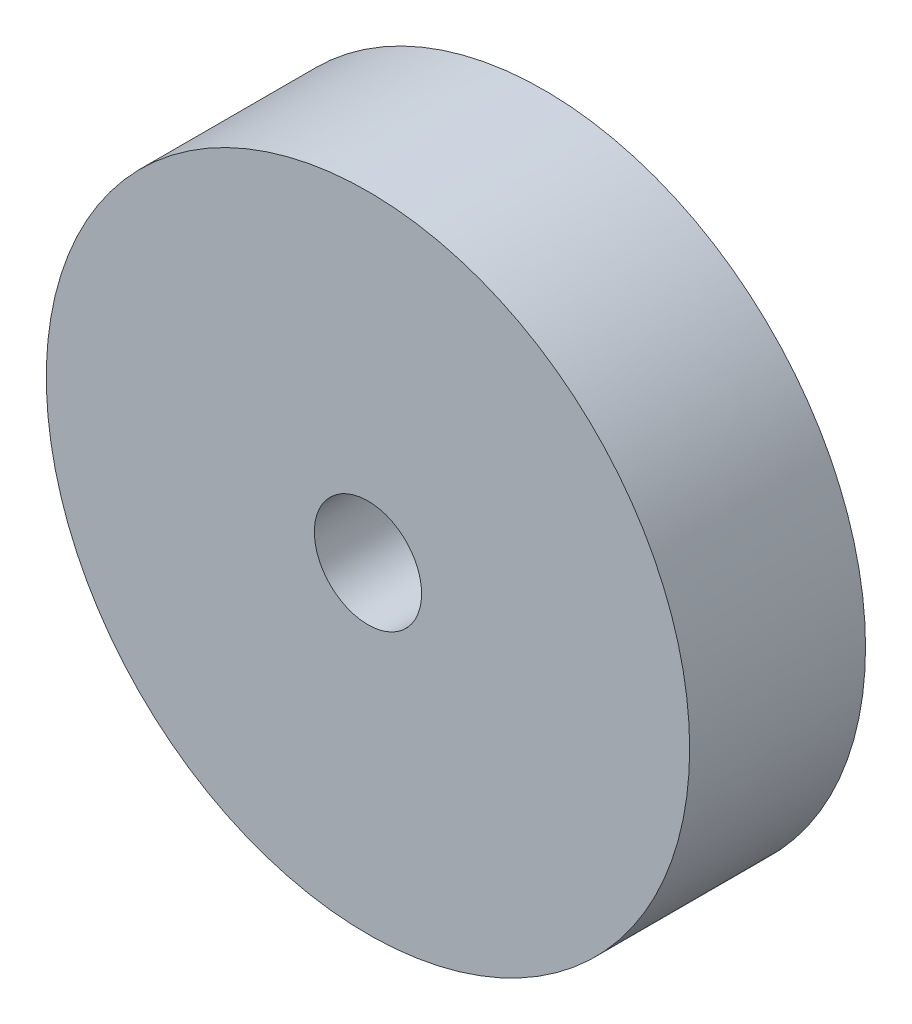
SolidWorks part; units mm, degrees
material "自訂玻璃纖維"
ref_plane "前基準面" through (0, 0, 0) normal (0, 0, 1) x (1, 0, 0)
ref_plane "上基準面" through (0, 0, 0) normal (0, 1, 0) x (1, 0, 0)
ref_plane "右基準面" through (0, 0, 0) normal (1, 0, 0) x (0, 0, -1)
sketch "草圖1" plane through (0, 0, 0) normal (0, 0, 1) x (1, 0, 0)
  circle A0 centre (-13.9029, 4.6452) radius 7.5
  circle A1 centre (-13.9029, 4.6452) radius 1.25
  point P13 (-13.9029, 4.6452)
  dimension "D1" = 15
  dimension "D2" = 2.5
extrude "填料-伸長1" add sketch "草圖1" along normal blind 4.1
